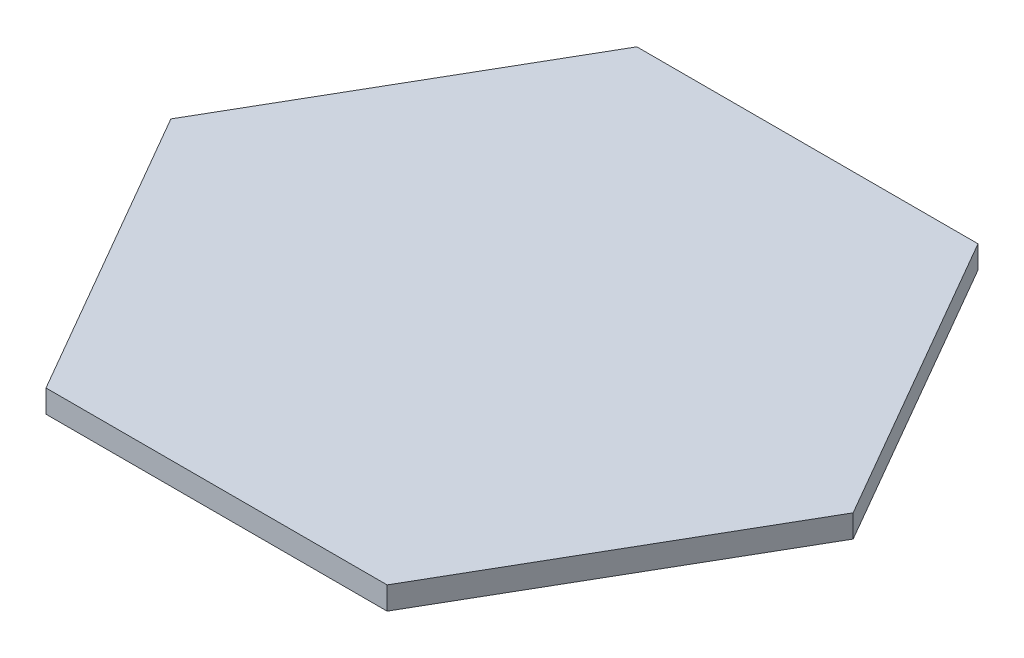
SolidWorks part; units mm, degrees
ref_plane "前视基准面" through (0, 0, 0) normal (0, 0, 1) x (1, 0, 0)
ref_plane "上视基准面" through (0, 0, 0) normal (0, 1, 0) x (1, 0, 0)
ref_plane "右视基准面" through (0, 0, 0) normal (1, 0, 0) x (0, 0, -1)
sketch "草图1" plane through (0, 0, 0) normal (0, 1, 0) x (1, 0, 0)
  line L1 (30, 0) -> (15, 25.9808)
  line L2 (15, 25.9808) -> (-15, 25.9808)
  line L3 (-15, 25.9808) -> (-30, 0)
  line L4 (-30, 0) -> (-15, -25.9808)
  line L5 (-15, -25.9808) -> (15, -25.9808)
  line L6 (15, -25.9808) -> (30, 0)
  circle A0 centre (0, 0) radius 25.9808 construction
  dimension "D1" = 30
extrude "凸台-拉伸1" add sketch "草图1" along normal blind 2
